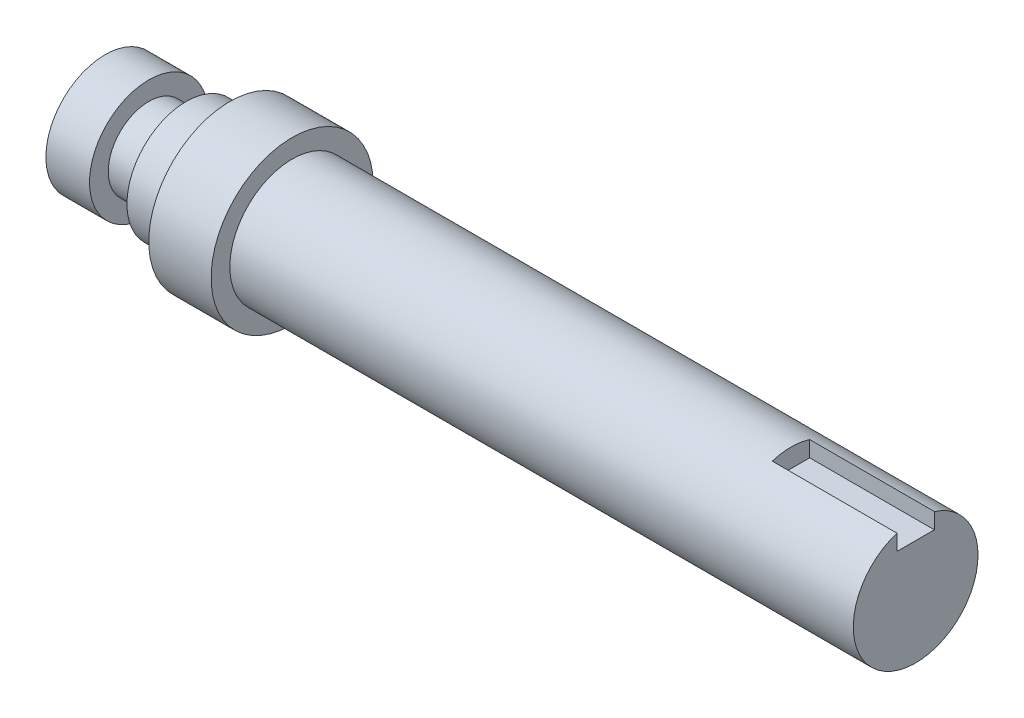
SolidWorks part; units mm, degrees
ref_plane "Front Plane" through (0, 0, 0) normal (0, 0, 1) x (1, 0, 0)
ref_plane "Top Plane" through (0, 0, 0) normal (0, 1, 0) x (1, 0, 0)
ref_plane "Right Plane" through (0, 0, 0) normal (1, 0, 0) x (0, 0, -1)
sketch "Sketch1" plane through (0, 0, 0) normal (0, 1, 0) x (1, 0, 0)
  line L0 (0, 0) -> (-3302, 0)
  line L1 (-3302, 0) -> (-3302, 241.3)
  line L2 (-3302, 241.3) -> (-3124.2, 241.3)
  line L3 (-3124.2, 241.3) -> (-3124.2, 165.1)
  line L4 (-3124.2, 165.1) -> (-2971.8, 165.1)
  line L5 (-2971.8, 165.1) -> (-2971.8, 241.3)
  line L6 (-2971.8, 241.3) -> (-2794, 241.3)
  line L7 (-2794, 241.3) -> (-2794, 330.2)
  line L8 (-2794, 330.2) -> (-2540, 330.2)
  line L9 (-2540, 330.2) -> (-2540, 254)
  line L10 (-2540, 254) -> (0, 254)
  line L11 (0, 254) -> (0, 0)
  dimension "D1" = 241.3
  dimension "D2" = 177.8
  dimension "D3" = 152.4
  dimension "D4" = 177.8
  dimension "D5" = 254
  dimension "D6" = 2540
  dimension "D7" = 76.2
  dimension "D8" = 254
  dimension "D9" = 76.2
  dimension "D10" = 241.3
revolve "Revolve1" add sketch "Sketch1" angle 360 about L0
sketch "Sketch4" plane through (0, 0, 0) normal (0, 0, 1) x (1, 0, 0)
  line L1 (0, 304.8) -> (-508, 304.8)
  line L2 (0, 304.8) -> (0, 177.8)
  line L3 (0, 177.8) -> (-508, 177.8)
  line L4 (-508, 304.8) -> (-508, 177.8)
  dimension "D1" = 76.2
  dimension "D2" = 127
  dimension "D3" = 508
  dimension "D4" = 508
extrude "Cut-Extrude1" cut sketch "Sketch4" against normal mid plane 152.4
